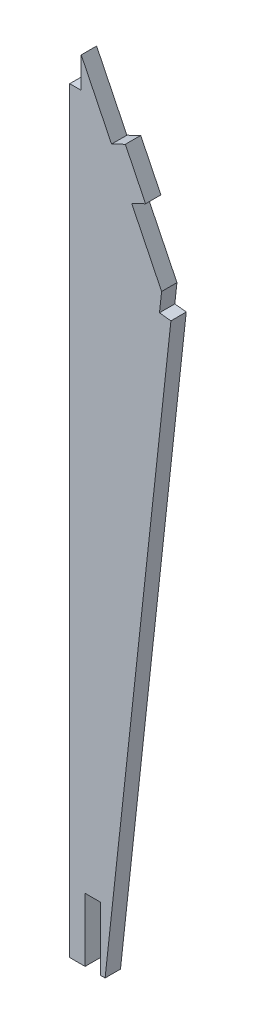
SolidWorks part; units mm, degrees
ref_plane "前视基准面" through (0, 0, 0) normal (0, 0, 1) x (1, 0, 0)
ref_plane "上视基准面" through (0, 0, 0) normal (0, 1, 0) x (1, 0, 0)
ref_plane "右视基准面" through (0, 0, 0) normal (1, 0, 0) x (0, 0, -1)
sketch "草图1" plane through (0, 0, 0) normal (0, 0, 1) x (1, 0, 0)
  line L0 (18.1386, 105.9039) -> (18.1386, 101.9039)
  line L1 (18.1386, 101.9039) -> (16.6386, 101.9039)
  line L2 (16.6386, 101.9039) -> (16.6386, 3.3546)
  line L3 (18.1386, 105.9039) -> (22.084, 97.8148)
  line L4 (22.084, 97.8148) -> (23.8815, 98.6915)
  line L5 (23.8815, 98.6915) -> (26.5118, 93.2987)
  line L6 (26.5118, 93.2987) -> (24.7142, 92.422)
  line L7 (24.7142, 92.422) -> (28.6022, 84.4504)
  line L8 (16.6386, 3.3546) -> (18.6386, 3.3546)
  line L9 (18.6386, 3.3546) -> (18.6386, 11.6046)
  line L10 (18.6386, 11.6046) -> (20.6386, 11.6046)
  line L11 (29.8158, 81.7485) -> (21.2457, 3.3546)
  line L12 (20.6386, 11.6046) -> (20.6386, 3.3546)
  line L13 (20.6386, 3.3546) -> (21.2457, 3.3546)
  line L14 (28.6022, 84.4504) -> (28.3246, 81.9115)
  line L15 (28.3246, 81.9115) -> (29.8158, 81.7485)
  line L16 (28.6022, 84.4504) -> (28.3246, 81.9115)
  line L17 (28.3246, 81.9115) -> (29.8158, 81.7485)
extrude "凸台-拉伸1" add sketch "草图1" along normal blind 2 contours L15 L14 L7 L6 L5 L4 L3 L0 L1 L2 L8 L9 L10 L12 L13 L11
